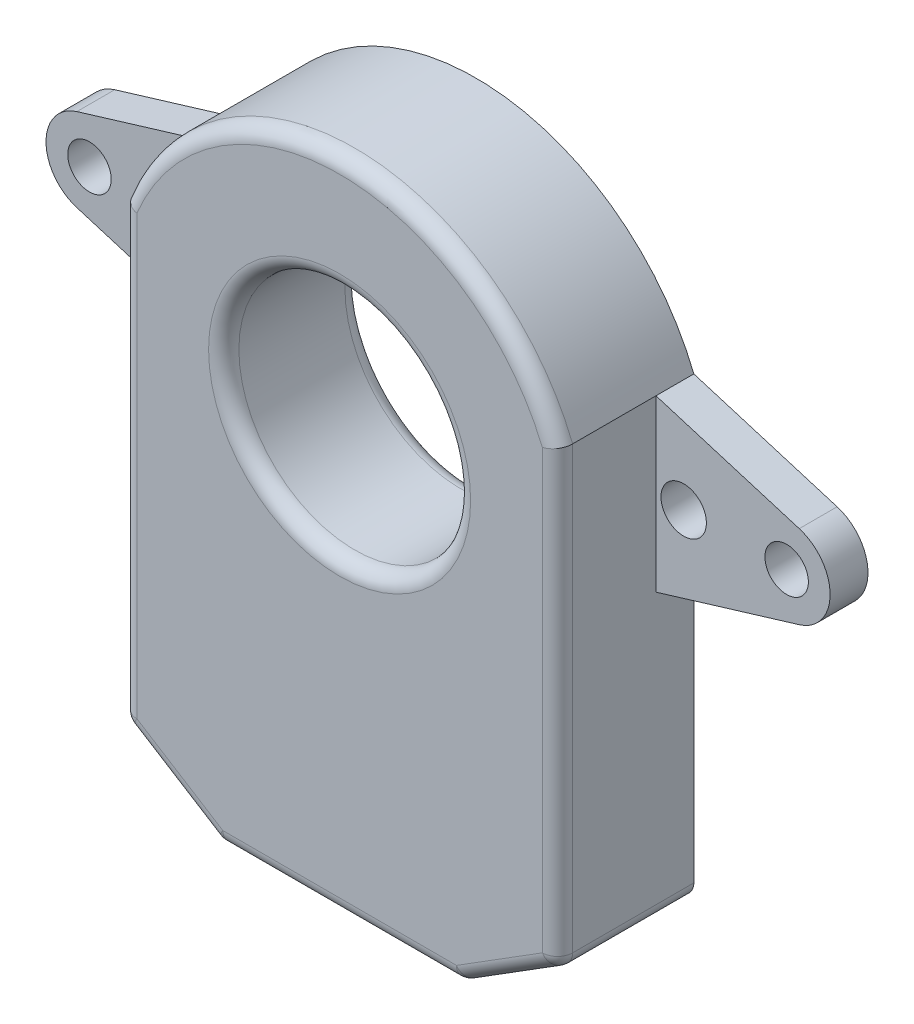
SolidWorks part; units mm, degrees
material "6061 Alloy"
ref_plane "Front Plane" through (0, 0, 0) normal (0, 0, 1) x (1, 0, 0)
ref_plane "Top Plane" through (0, 0, 0) normal (0, 1, 0) x (1, 0, 0)
ref_plane "Right Plane" through (0, 0, 0) normal (1, 0, 0) x (0, 0, -1)
sketch "Sketch1" plane through (0, 0, 0) normal (0, 0, 1) x (1, 0, 0)
  line L0 (6.385, 0) -> (22.385, 0)
  line L1 (22.385, 0) -> (28.77, 4)
  line L2 (6.385, 0) -> (0, 4)
  line L3 (0, 4) -> (0, 33.6525)
  line L4 (28.77, 33.6525) -> (28.77, 4)
  arc A0 (0, 33.6525) -> (28.77, 33.6525) centre (14.385, 27.88) cw
  circle A1 centre (14.385, 28.04) radius 7.65
  point P8 (14.385, 43.38)
  point P11 (14.385, 0)
  dimension "D3" = 15.5
  dimension "D1" = 28.77
  dimension "D5" = 15.34
  dimension "D6" = 15.3
  dimension "D2" = 4
  dimension "D4" = 16
  dimension "D7" = 43.38
  dimension "D8" = 6.385
extrude "Boss-Extrude1" add sketch "Sketch1" along normal blind 9
fillet "Fillet1" radius 1 12 edges at (22.035, 28.04, 0) (22.035, 28.04, 9) (14.385, 43.38, 9) (22.385, 0, 4.5) (6.385, 0, 4.5) (0, 4, 4.5) (28.77, 4, 4.5) (3.1925, 2, 9) (14.385, 0, 9) (25.5775, 2, 9) (28.77, 18.8263, 9) (0, 18.8263, 9)
sketch "Sketch2" plane through (0, 0, 0) normal (0, 0, -1) x (-1, 0, 0)
  line L0 (-1014.385, 28.04) -> (48985.615, 28.04) construction
  line L1 (-28.77, 33.6525) -> (-38.2296, 30.7867)
  line L2 (-28.77, 33.6525) -> (-28.77, 22.4275)
  line L3 (-28.77, 4.5536) -> (-28.77, 33.6525) construction
  line L4 (-28.77, 22.4275) -> (-38.2296, 25.2933)
  line L5 (-14.385, -971.96) -> (-14.385, 49028.04) construction
  line L6 (0, 22.4275) -> (9.4596, 25.2933)
  line L7 (0, 33.6525) -> (0, 22.4275)
  line L8 (0, 33.6525) -> (9.4596, 30.7867)
  circle A0 centre (-30.6, 28.04) radius 1.5
  circle A1 centre (-37.3975, 28.04) radius 1.435
  circle A2 centre (-14.385, 28.04) radius 7.65 construction
  arc A3 (-38.2296, 30.7867) -> (-38.2296, 25.2933) centre (-37.3975, 28.04) ccw
  arc A4 (9.4596, 30.7867) -> (9.4596, 25.2933) centre (8.6275, 28.04) cw
  circle A5 centre (8.6275, 28.04) radius 1.435
  circle A6 centre (1.83, 28.04) radius 1.5
  point P18 (-28.77, 28.04)
  point P28 (0, 28.04)
  dimension "D1" = 3
  dimension "D2" = 2.87
  dimension "D3" = 16.215
  dimension "D4" = 23.0125
  dimension "D7" = 2.87
extrude "Boss-Extrude2" add sketch "Sketch2" against normal blind 2.5
